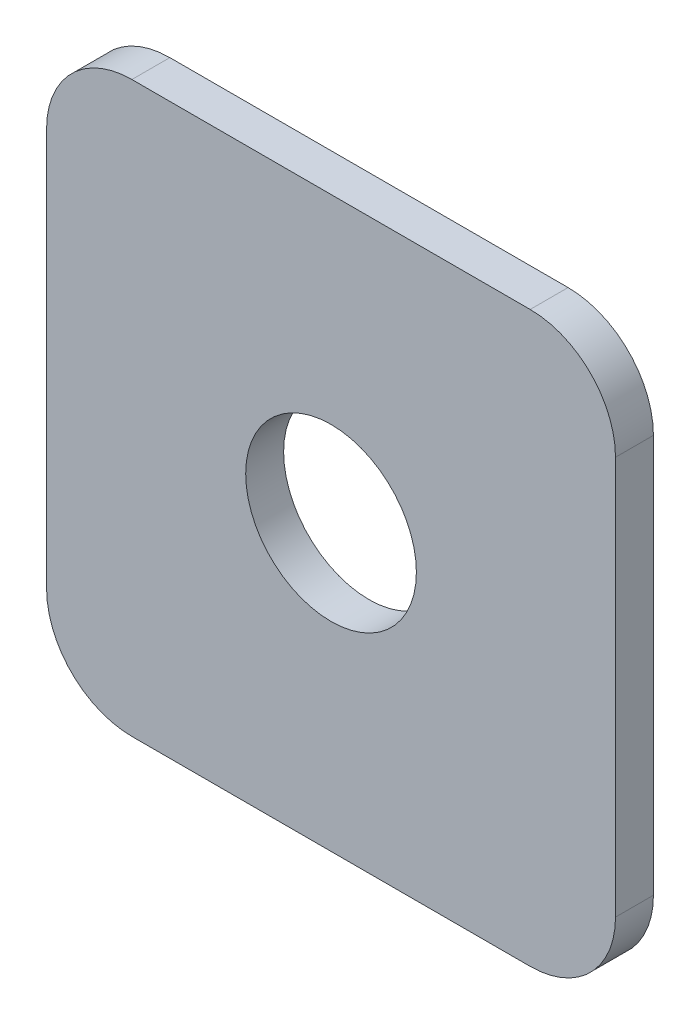
SolidWorks part; units mm, degrees
ref_plane "Plan de face" through (0, 0, 0) normal (0, 0, 1) x (1, 0, 0)
ref_plane "Plan de dessus" through (0, 0, 0) normal (0, 1, 0) x (1, 0, 0)
ref_plane "Plan de droite" through (0, 0, 0) normal (1, 0, 0) x (0, 0, -1)
sketch "Esquisse1" plane through (0, 0, 0) normal (0, 0, 1) x (1, 0, 0)
  line L0 (0, 75) -> (150, 75) construction
  line L1 (0, 0) -> (150, 0)
  line L2 (0, 0) -> (0, 150)
  line L3 (0, 150) -> (150, 150)
  line L4 (150, 0) -> (150, 150)
  circle A0 centre (75, 75) radius 22.5
  dimension "D3" = 45
  dimension "D1" = 150
  dimension "D2" = 150
extrude "Boss.-Extru.1" add sketch "Esquisse1" along normal blind 10
fillet "Congé1" radius 22.5 4 edges at (0, 150, 5) (0, 0, 5) (150, 0, 5) (150, 150, 5)
